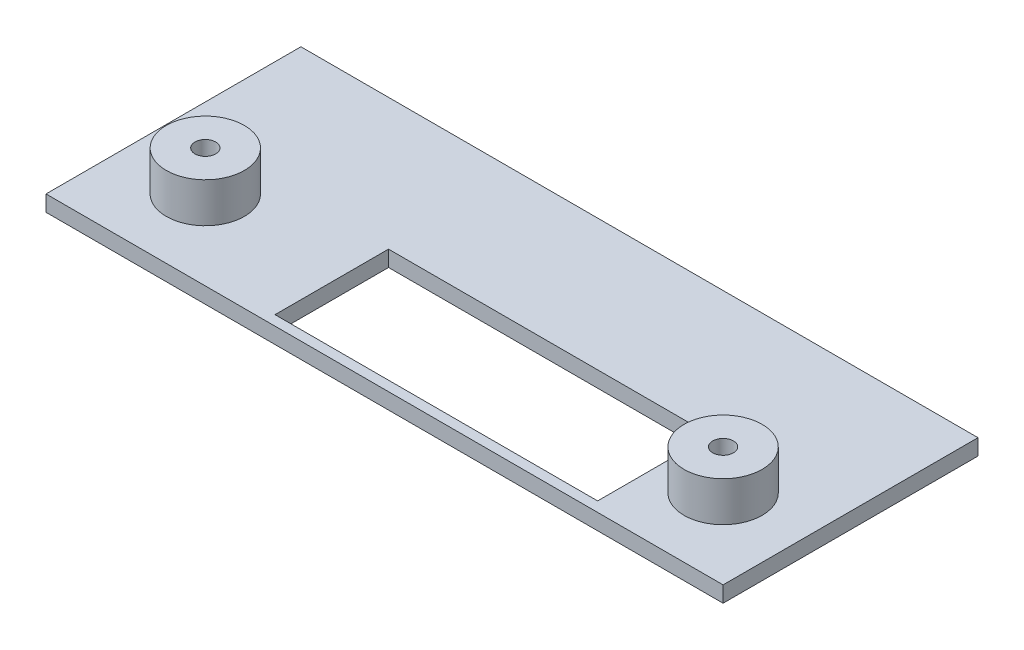
SolidWorks part; units mm, degrees
ref_plane "Front Plane" through (0, 0, 0) normal (0, 0, 1) x (1, 0, 0)
ref_plane "Top Plane" through (0, 0, 0) normal (0, 1, 0) x (1, 0, 0)
ref_plane "Right Plane" through (0, 0, 0) normal (1, 0, 0) x (0, 0, -1)
sketch "Sketch1" plane through (0, 0, 0) normal (0, 1, 0) x (1, 0, 0)
  line L0 (0, 0) -> (0, 64)
  line L1 (0, 0) -> (170, 0)
  line L2 (170, 0) -> (170, 64)
  line L3 (0, 64) -> (170, 64)
  line L4 (55, 31) -> (55, 2.5)
  line L5 (55, 31) -> (136, 31)
  line L6 (136, 31) -> (136, 2.5)
  line L7 (55, 2.5) -> (136, 2.5)
  circle A0 centre (20, 20) radius 10
  circle A1 centre (150, 20) radius 10
  dimension "D5" = 20
  dimension "D6" = 20
  dimension "D1" = 170
  dimension "D2" = 64
  dimension "D3" = 2.5
  dimension "D4" = 28.5
  dimension "D7" = 34
  dimension "D8" = 81
  dimension "D9" = 20
  dimension "D10" = 20
  dimension "D11" = 20
  dimension "D12" = 20
  dimension "D13" = 0
extrude "Boss-Extrude1" add sketch "Sketch1" along normal blind 4
sketch "Sketch2" plane through (0, 4, 0) normal (0, 1, 0) x (1, 0, 0)
  circle A0 centre (20, 20) radius 9.8
  circle A1 centre (20, 20) radius 10
  circle A2 centre (150, 20) radius 10
  circle A3 centre (150, 20) radius 9.8
  dimension "D1" = 19.6
  dimension "D2" = 19.6
  dimension "D3" = 20
  dimension "D4" = 20
extrude "Boss-Extrude2" add sketch "Sketch2" against normal blind 4
sketch "Sketch3" plane through (0, 4, 0) normal (0, 1, 0) x (1, 0, 0)
  circle A0 centre (20, 20) radius 9.8
  circle A1 centre (150, 20) radius 9.8
  dimension "D1" = 19.6
  dimension "D2" = 19.6
extrude "Boss-Extrude3" add sketch "Sketch3" along normal blind 10 separate body
sketch "Sketch4" plane through (0, 4, 0) normal (0, -1, 0) x (1, 0, 0)
  line L1 (22.6269, -15.45) -> (17.3731, -15.45)
  line L2 (17.3731, -15.45) -> (14.7461, -20)
  line L3 (14.7461, -20) -> (17.3731, -24.55)
  line L4 (17.3731, -24.55) -> (22.6269, -24.55)
  line L5 (22.6269, -24.55) -> (25.2539, -20)
  line L6 (25.2539, -20) -> (22.6269, -15.45)
  line L7 (152.6269, -15.45) -> (147.3731, -15.45)
  line L8 (147.3731, -15.45) -> (144.7461, -20)
  line L9 (144.7461, -20) -> (147.3731, -24.55)
  line L10 (147.3731, -24.55) -> (152.6269, -24.55)
  line L11 (152.6269, -24.55) -> (155.2539, -20)
  line L12 (155.2539, -20) -> (152.6269, -15.45)
  circle A0 centre (20, -20) radius 4.55 construction
  circle A1 centre (20, -20) radius 9.8
  circle A2 centre (150, -20) radius 4.55 construction
  circle A3 centre (150, -20) radius 9.8
  circle A4 centre (20, -20) radius 2.6
  circle A5 centre (150, -20) radius 2.6
  circle M15 centre (20, -20) radius 9.8
  dimension "D1" = 9.1
  dimension "D2" = 19.6
  dimension "D3" = 9.1
  dimension "D4" = 19.6
  dimension "D5" = 5.2
  dimension "D6" = 5.2
extrude "Boss-Extrude4" add sketch "Sketch4" along normal up to surface (4 mm away) contours L6 L5 L4 L3 L2 L1 M15 | A4 | A3 L12 L11 L10 L9 L8 L7 | A5 up to face at (85, 0, -32)
sketch "Sketch5" plane through (0, 0, 0) normal (0, -1, 0) x (1, 0, 0)
  circle A0 centre (20, -20) radius 2.6
  circle A1 centre (150, -20) radius 2.6
  dimension "D1" = 5.2
  dimension "D2" = 5.2
extrude "Cut-Extrude1" cut sketch "Sketch5" against normal blind 47
